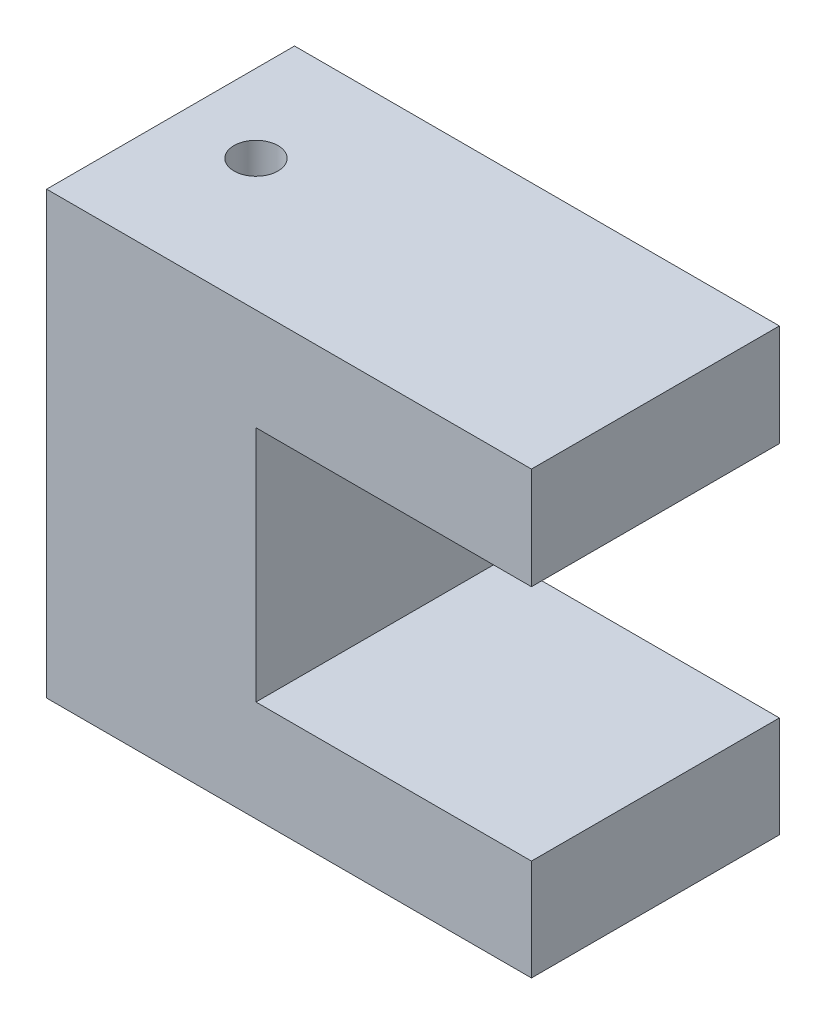
SolidWorks part; units mm, degrees
ref_plane "Ön Düzlem" through (0, 0, 0) normal (0, 0, 1) x (1, 0, 0)
ref_plane "Üst Düzlem" through (0, 0, 0) normal (0, 1, 0) x (1, 0, 0)
ref_plane "Sağ Düzlem" through (0, 0, 0) normal (1, 0, 0) x (0, 0, -1)
sketch "Çizim1" plane through (0, 0, 0) normal (0, 0, 1) x (1, 0, 0)
  line L0 (44, 40) -> (44, -40)
  line L1 (44, 40) -> (-44, 40)
  line L2 (-44, 40) -> (-44, -40)
  line L3 (-44, -40) -> (44, -40)
  point P2 (0, 40)
  point P5 (-44, 0)
  dimension "D1" = 80
  dimension "D2" = 88
extrude "Yükseklik-Ekstrüzyon1" add sketch "Çizim1" along normal blind 45
sketch "Çizim2" plane through (0, 0, 45) normal (0, 0, 1) x (1, 0, 0)
  line L8 (44, -40) -> (44, 40) construction
  line L9 (44, 21.5) -> (-6, 21.5)
  line L10 (44, 21.5) -> (44, -21.6191)
  line L11 (44, -21.6191) -> (-6, -21.6191)
  line L12 (-6, 21.5) -> (-6, -21.6191)
  line L13 (-2, 21.5) -> (32.3, 21.5) construction
  dimension "D1" = 50
extrude "Kes-Ekstrüzyon1" cut sketch "Çizim2" against normal through all
sketch "Çizim3" plane through (0, 40, 0) normal (0, 1, 0) x (1, 0, 0)
  circle A0 centre (-29.85, -21.15) radius 4.003
extrude "Kes-Ekstrüzyon2" cut sketch "Çizim3" against normal through all
